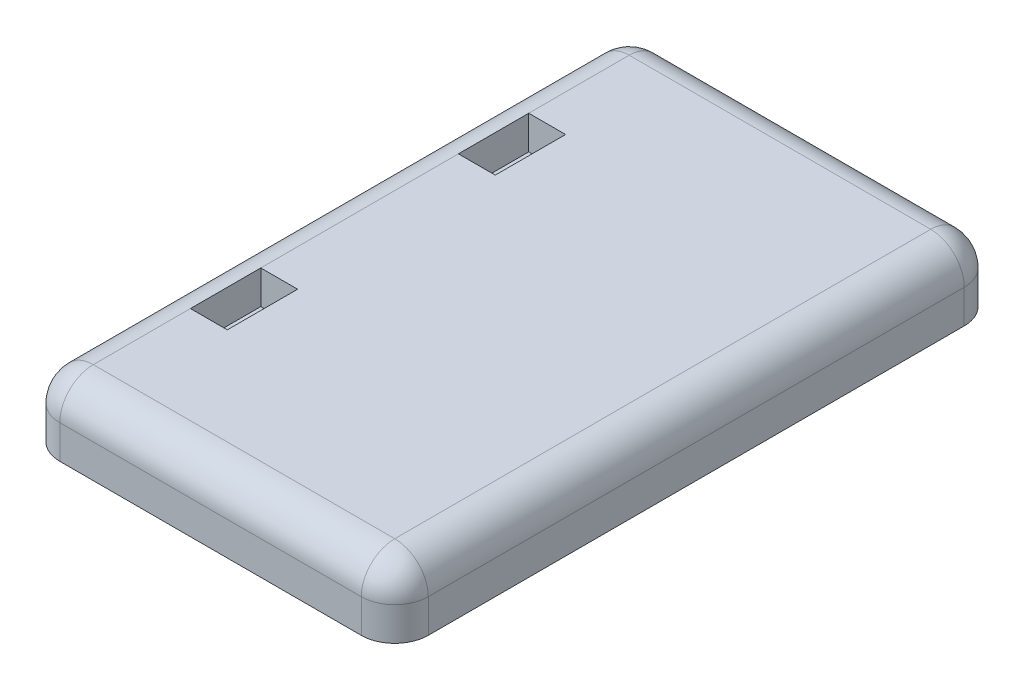
SolidWorks part; units mm, degrees
ref_plane "前视基准面" through (0, 0, 0) normal (0, 0, 1) x (1, 0, 0)
ref_plane "上视基准面" through (0, 0, 0) normal (0, 1, 0) x (1, 0, 0)
ref_plane "右视基准面" through (0, 0, 0) normal (1, 0, 0) x (0, 0, -1)
other "Configuration Table"
sketch "草图2" plane through (0, 0, 0) normal (0, 1, 0) x (1, 0, 0)
  line L1 (-27.5, -45) -> (27.5, -45)
  line L2 (-27.5, -45) -> (-27.5, 45)
  line L3 (-27.5, 45) -> (27.5, 45)
  line L4 (27.5, -45) -> (27.5, 45)
  line L5 (-27.5, -45) -> (27.5, 45) construction
  line L6 (-27.5, 45) -> (27.5, -45) construction
  point P0 (0, 0)
  dimension "D1" = 90
  dimension "D2" = 55
extrude "凸台-拉伸1" add sketch "草图2" along normal blind 10
fillet "圆角1" radius 5 1 edges at (-27.5, 10, 0)
fillet "圆角2" radius 5 3 edges at (-27.5, 2.5, -45) (-26.0355, 8.5355, -45) (2.5, 10, -45)
fillet "圆角3" radius 5 3 edges at (27.5, 2.5, -45) (27.5, 8.5355, -43.5355) (27.5, 10, 2.5)
fillet "圆角4" radius 5 5 edges at (-27.5, 2.5, 45) (-26.0355, 8.5355, 45) (27.5, 2.5, 45) (26.0355, 8.5355, 45) (0, 10, 45)
sketch "草图3" plane through (0, 10, 0) normal (0, 1, 0) x (1, 0, 0)
  line L1 (-22.5, 25) -> (-17, 25)
  line L2 (-22.5, 25) -> (-22.5, 14.5)
  line L3 (-22.5, 14.5) -> (-17, 14.5)
  line L4 (-17, 25) -> (-17, 14.5)
  line L5 (-22.5, 25) -> (-17, 14.5) construction
  line L6 (-22.5, 14.5) -> (-17, 25) construction
  line L7 (-22.5, -15) -> (-17, -15)
  line L8 (-22.5, -15) -> (-22.5, -25.5)
  line L9 (-22.5, -25.5) -> (-17, -25.5)
  line L10 (-17, -15) -> (-17, -25.5)
  line L11 (-22.5, -15) -> (-17, -25.5) construction
  line L12 (-22.5, -25.5) -> (-17, -15) construction
  point P0 (-19.75, 19.75)
  point P5 (-19.75, -20.25)
  point P10 (0, 0)
  dimension "D8" = 40
  dimension "D1" = 5.5
  dimension "D2" = 10.5
  dimension "D3" = 5.5
  dimension "D4" = 10.5
  dimension "D5" = 14.5
  dimension "D7" = 17
extrude "切除-拉伸1" cut sketch "草图3" against normal blind 5 contours L4 L1 L2 L3 | L8 L7 L10 L9
